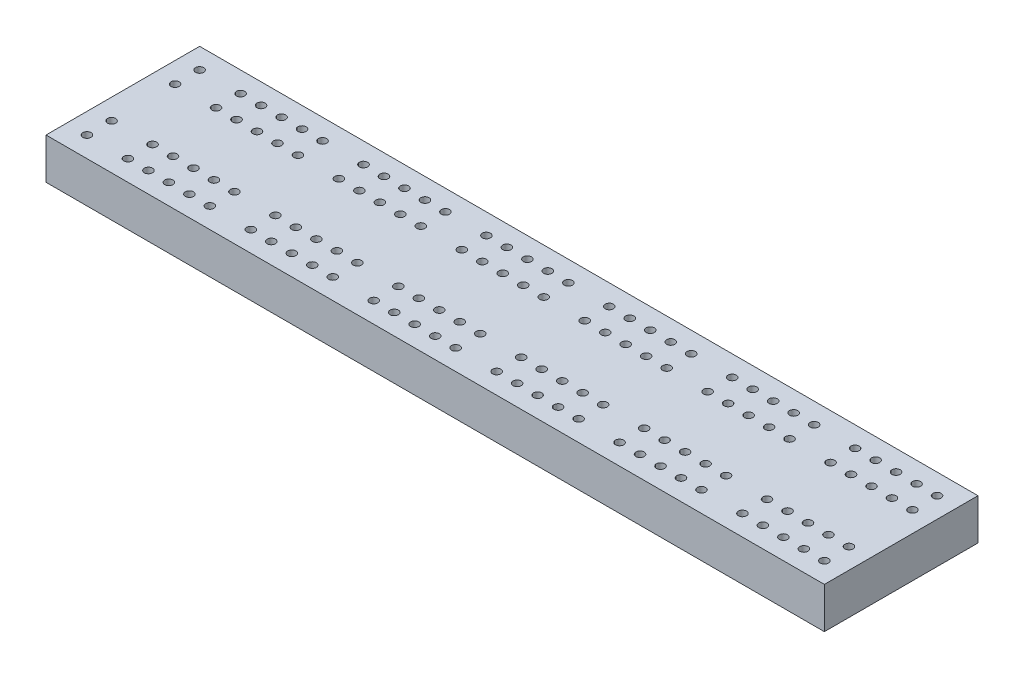
SolidWorks part; units mm, degrees
ref_plane "Front Plane" through (0, 0, 0) normal (0, 0, 1) x (1, 0, 0)
ref_plane "Top Plane" through (0, 0, 0) normal (0, 1, 0) x (1, 0, 0)
ref_plane "Right Plane" through (0, 0, 0) normal (1, 0, 0) x (0, 0, -1)
sketch "Sketch1" plane through (0, 0, 0) normal (0, 1, 0) x (1, 0, 0)
  line L1 (0, -37.5) -> (380, -37.5)
  line L2 (0, -37.5) -> (0, 37.5)
  line L3 (0, 37.5) -> (380, 37.5)
  line L4 (380, -37.5) -> (380, 37.5)
  dimension "D1" = 75
  dimension "D2" = 380
extrude "Boss-Extrude1" add sketch "Sketch1" along normal blind 20
hole_wizard "Ø4.0 (4) Diameter Hole1" positions "Sketch2" profile "Sketch3" hole size "Ø4.0" standard "ANSI Metric" end condition through all
sketch "Sketch2" plane through (0, 20, 0) normal (0, 1, 0) x (1, 0, 0)
  line L0 (380, 37.5) -> (0, 37.5) construction
  line L1 (0, 37.5) -> (0, -37.5) construction
  point P0 (10, 27.5)
  dimension "D1" = 10
  dimension "D2" = 10
sketch "Sketch3" plane through (10, 20, -27.5) normal (1, 0, 0) x (0, 0, 1)
  line L0 (0, 0) -> (0, 20)
  line L1 (0, 20) -> (2, 20)
  line L2 (2, 20) -> (2, 0)
  line L5 (2, 0) -> (0, 0)
  line L11 (0, -6.35) -> (0, 107.95) construction
  dimension "Thru Hole Dia." = 4
  dimension "Thru Hole Depth" = 20
pattern_linear "LPattern1" count 37 spacing 10 along (1, 0, 0) count 2 spacing 12 along (0, 0, 1) skipping (1, 0), (1, 1), (7, 0), (7, 1), (13, 0), (13, 1), (19, 0), (19, 1), (25, 0), (25, 1), (31, 0), (31, 1) of "Ø4.0 (4) Diameter Hole1"
mirror "Mirror1" about plane through (0, 0, 0) normal (0, 0, 1) of "LPattern1", "Ø4.0 (4) Diameter Hole1"
